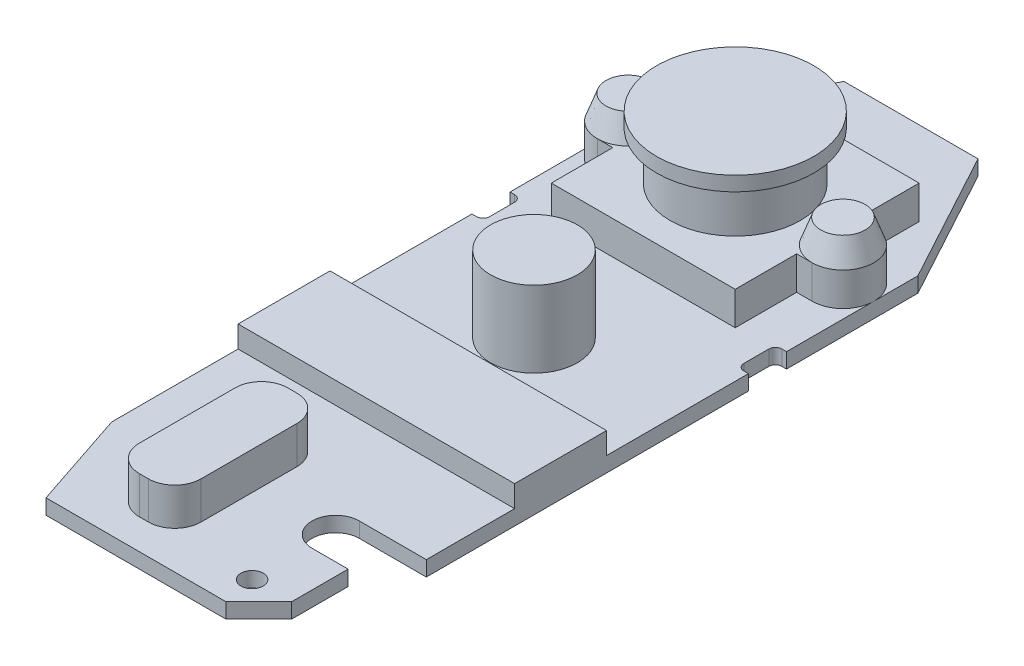
SolidWorks part; units mm, degrees
ref_plane "Спереди" through (0, 0, 0) normal (0, 0, 1) x (1, 0, 0)
ref_plane "Сверху" through (0, 0, 0) normal (0, 1, 0) x (1, 0, 0)
ref_plane "Справа" through (0, 0, 0) normal (1, 0, 0) x (0, 0, -1)
other "Configuration Table"
sketch "Эскиз1" plane through (0, 0, 0) normal (0, 1, 0) x (1, 0, 0)
  line L0 (5.1, 17.8012) -> (10.525, 7.8012)
  line L1 (-5.1, 17.8012) -> (5.1, 17.8012)
  line L2 (-10.525, 7.8012) -> (-10.525, -2.1988)
  line L3 (-8.025, -40.0188) -> (5.675, -40.0188)
  line L4 (10.525, 7.8012) -> (10.525, -2.1988)
  line L5 (10.525, -2.1988) -> (10.175, -2.1988)
  line L6 (9.675, -2.6988) -> (9.675, -4.5988)
  line L7 (-5.1, 17.8012) -> (-10.525, 7.8012)
  line L8 (10.175, -5.0988) -> (10.525, -5.0988)
  line L9 (0, 17.8012) -> (0, -40.0188) construction
  line L10 (-10.525, -2.1988) -> (-10.175, -2.1988)
  line L11 (-9.675, -2.6988) -> (-9.675, -4.5988)
  line L12 (-10.175, -5.0988) -> (-10.525, -5.0988)
  line L13 (-10.525, -5.0988) -> (-10.525, -32.5188)
  line L14 (10.525, -5.0988) -> (10.525, -29.6188)
  line L15 (10.525, -29.6188) -> (5.425, -29.6188)
  line L16 (8.175, -33.2188) -> (5.425, -33.2188)
  line L19 (8.175, -33.2188) -> (8.175, -37.5188)
  line L20 (8.175, -37.5188) -> (5.675, -40.0188)
  line L21 (-10.525, -32.5188) -> (-8.025, -40.0188)
  arc A0 (10.175, -5.0988) -> (9.675, -4.5988) centre (10.175, -4.5988) cw
  arc A1 (9.675, -2.6988) -> (10.175, -2.1988) centre (10.175, -2.6988) cw
  arc A2 (-9.675, -2.6988) -> (-10.175, -2.1988) centre (-10.175, -2.6988) ccw
  arc A3 (-10.175, -5.0988) -> (-9.675, -4.5988) centre (-10.175, -4.5988) ccw
  arc A4 (5.425, -33.2188) -> (5.425, -29.6188) centre (5.425, -31.4188) cw
  circle A5 centre (5.2117, -37.5688) radius 0.85
  circle A6 centre (-4.9036, 13.8012) radius 0.85
  point P0 (0, 0)
  point P3 (-10.525, -40.0188)
  point P17 (0, 17.8012)
  point P28 (8.175, -40.0188)
  dimension "D7" = 0.5
  dimension "D10" = 6.9
  dimension "D16" = 1.7
  dimension "D18" = 1.21
  dimension "D19" = 1.6
  dimension "D20" = 1.23
  dimension "D1" = 57.82
  dimension "D2" = 21.05
  dimension "D3" = 10.2
  dimension "D4" = 10
  dimension "D5" = 2.9
  dimension "D6" = 0.85
  dimension "D8" = 20
  dimension "D9" = 3.6
  dimension "D11" = 6.8
  dimension "D12" = 2.35
  dimension "D13" = 7.5
  dimension "D14" = 2.5
  dimension "D15" = 7.8012
  dimension "D17" = 2.5
  dimension "D21" = 3.15
extrude "Бобышка-Вытянуть1" add sketch "Эскиз1" along normal blind 1.15
sketch "Эскиз2" plane through (0, 1.15, 0) normal (0, 1, 0) x (1, 0, 0)
  line L0 (5.1, 17.8012) -> (-5.1, 17.8012) construction
  line L1 (-7, 11.4212) -> (7, 11.4212)
  line L2 (-7, 11.4212) -> (-7, 6.7977)
  line L3 (-7, -2.5788) -> (7, -2.5788)
  line L4 (7, 11.4212) -> (7, 6.7977)
  line L5 (-7, 11.4212) -> (7, -2.5788) construction
  line L6 (-7, -2.5788) -> (7, 11.4212) construction
  line L7 (-10.525, 7.8012) -> (-10.525, -2.1988) construction
  line L8 (-8.175, 6.7977) -> (-7, 6.7977)
  line L9 (-8.175, 2.0977) -> (-7, 2.0977)
  line L10 (-7, 2.0977) -> (-7, -2.5788)
  line L11 (0, 11.4212) -> (0, -2.5788) construction
  line L12 (8.175, 2.0977) -> (7, 2.0977)
  line L13 (8.175, 6.7977) -> (7, 6.7977)
  line L14 (7, 2.0977) -> (7, -2.5788)
  line L15 (10.525, -29.6188) -> (10.525, -5.0988) construction
  line L16 (5.425, -29.6188) -> (10.525, -29.6188) construction
  arc A0 (-8.175, 6.7977) -> (-8.175, 2.0977) centre (-8.175, 4.4477) ccw
  arc A1 (8.175, 6.7977) -> (8.175, 2.0977) centre (8.175, 4.4477) cw
  point P0 (0, 4.4212)
  dimension "D3" = 4.7
  dimension "D4" = 34.0665
  dimension "D1" = 14
  dimension "D2" = 6.38
  dimension "D5" = 1.175
extrude "Бобышка-Вытянуть2" add sketch "Эскиз2" along normal blind 2.54
sketch "Эскиз3" plane through (0, 3.69, 0) normal (0, 1, 0) x (1, 0, 0)
  line L0 (-7, 11.4212) -> (7, -2.5788) construction
  line L1 (-7, -2.5788) -> (7, 11.4212) construction
  circle A0 centre (0, 4.4212) radius 4.95
  dimension "D1" = 9.9
extrude "Бобышка-Вытянуть3" add sketch "Эскиз3" along normal blind 3.65
sketch "Эскиз4" plane through (0, 7.34, 0) normal (0, 1, 0) x (1, 0, 0)
  circle A0 centre (0, 4.4212) radius 5.985
  dimension "D1" = 11.97
extrude "Бобышка-Вытянуть4" add sketch "Эскиз4" along normal blind 1.1
sketch "Эскиз5" plane through (0, 3.69, 0) normal (0, 1, 0) x (1, 0, 0)
  circle A0 centre (-8.175, 4.4477) radius 2.35
  dimension "D1" = 4.7
extrude "Бобышка-Вытянуть5" add sketch "Эскиз5" along normal blind 1.825 draft 20
mirror "Зеркальное отражение1" about plane through (0, 0, 0) normal (1, 0, 0) of "Бобышка-Вытянуть5"
sketch "Эскиз6" plane through (0, 1.15, 0) normal (0, 1, 0) x (1, 0, 0)
  line L1 (5.1, 17.8012) -> (-5.1, 17.8012) construction
  circle A0 centre (0, -10.8988) radius 3.3
  point P4 (0, 0)
  dimension "D1" = 6.6
  dimension "D2" = 32
extrude "Бобышка-Вытянуть6" add sketch "Эскиз6" along normal blind 5.8
sketch "Эскиз7" plane through (0, 1.15, 0) normal (0, 1, 0) x (1, 0, 0)
  line L0 (-10.525, -5.0988) -> (-10.525, -32.5188) construction
  line L1 (-10.525, -15.8988) -> (10.525, -15.8988)
  line L2 (-10.525, -15.8988) -> (-10.525, -22.8988)
  line L3 (-10.525, -22.8988) -> (10.525, -22.8988)
  line L4 (10.525, -15.8988) -> (10.525, -22.8988)
  line L5 (10.525, -29.6188) -> (10.525, -5.0988) construction
  circle A0 centre (0, -10.8988) radius 3.3 construction
  dimension "D2" = 5
  dimension "D1" = 7
extrude "Бобышка-Вытянуть7" add sketch "Эскиз7" along normal blind 1.65
sketch "Эскиз8" plane through (0, 1.15, 0) normal (0, 1, 0) x (1, 0, 0)
  line L0 (-10.525, -22.8988) -> (-10.525, -32.5188) construction
  line L1 (-3.225, -26.4188) -> (-2.525, -26.4188)
  line L2 (-5.225, -28.4188) -> (-5.225, -35.7188)
  line L3 (-3.225, -37.7188) -> (-2.525, -37.7188)
  line L4 (-0.525, -28.4188) -> (-0.525, -35.7188)
  line L5 (-8.025, -40.0188) -> (5.675, -40.0188) construction
  arc A0 (-2.525, -37.7188) -> (-0.525, -35.7188) centre (-2.525, -35.7188) ccw
  arc A1 (-3.225, -37.7188) -> (-5.225, -35.7188) centre (-3.225, -35.7188) cw
  arc A2 (-2.525, -26.4188) -> (-0.525, -28.4188) centre (-2.525, -28.4188) cw
  arc A3 (-3.225, -26.4188) -> (-5.225, -28.4188) centre (-3.225, -28.4188) ccw
  point P10 (-0.525, -37.7188)
  point P13 (-5.225, -37.7188)
  point P16 (-0.525, -26.4188)
  dimension "D5" = 2
  dimension "D1" = 11.3
  dimension "D2" = 4.7
  dimension "D3" = 10
  dimension "D4" = 13.6
extrude "Бобышка-Вытянуть8" add sketch "Эскиз8" along normal blind 2.85
sketch "Эскиз9" plane through (0, 0, 0) normal (0, -1, 0) x (1, 0, 0)
  line L0 (-10.525, 5.0988) -> (-10.525, 32.5188) construction
  line L1 (-8.975, 31.1688) -> (-2.975, 31.1688)
  line L2 (-8.975, 31.1688) -> (-8.975, 26.8688)
  line L3 (-8.975, 26.8688) -> (-2.975, 26.8688)
  line L4 (-2.975, 31.1688) -> (-2.975, 26.8688)
  line L5 (-8.025, 40.0188) -> (5.675, 40.0188) construction
  dimension "D1" = 6
  dimension "D2" = 4.3
  dimension "D3" = 7.55
  dimension "D4" = 13.15
extrude "Бобышка-Вытянуть9" add sketch "Эскиз9" along normal blind 2.95
